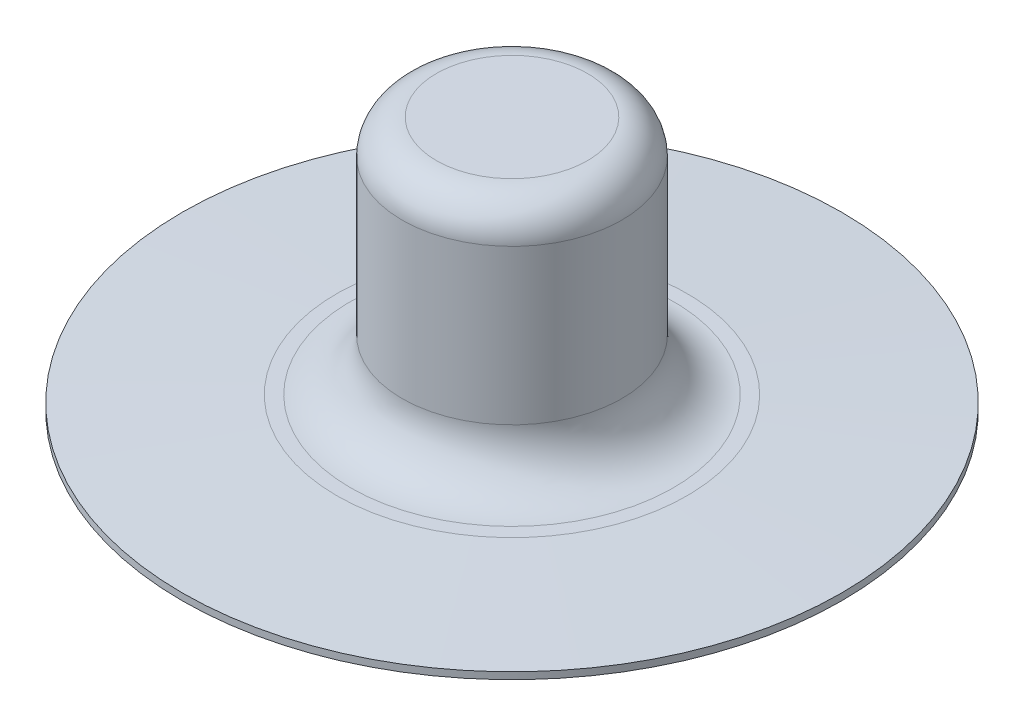
SolidWorks part; units mm, degrees
ref_plane "Front Plane" through (0, 0, 0) normal (0, 0, 1) x (1, 0, 0)
ref_plane "Top Plane" through (0, 0, 0) normal (0, 1, 0) x (1, 0, 0)
ref_plane "Right Plane" through (0, 0, 0) normal (1, 0, 0) x (0, 0, -1)
sketch "Croquis1" plane through (0, 0, 0) normal (0, 1, 0) x (1, 0, 0)
  circle A0 centre (0, 0) radius 4.8
  dimension "D1" = 9.6
extrude "Saliente-Extruir1" add sketch "Croquis1" along normal blind 0.2
sketch "Croquis2" plane through (0, 0.2, 0) normal (0, 1, 0) x (1, 0, 0)
  circle A0 centre (0, 0) radius 1.6
  dimension "D1" = 3.2
extrude "Saliente-Extruir2" add sketch "Croquis2" along normal blind 3.5
fillet "Redondeo1" radius 0.5 1 edges at (0, 3.7, 1.6)
fillet "Redondeo2" radius 0.75 1 edges at (0, 0.2, 1.6)
sketch "Croquis3" plane through (0, 0, 0) normal (0, -1, 0) x (1, 0, 0)
  circle A0 centre (0, 0) radius 1.15
  dimension "D1" = 2.3
extrude "Cortar-Extruir1" cut sketch "Croquis3" against normal blind 3
fillet "Redondeo3" radius 1 1 edges at (0, 0, -1.15)
chamfer "Chaflán1" distance 0.1 distance2 2.25 1 edges at (0, 0.2, 4.8)
